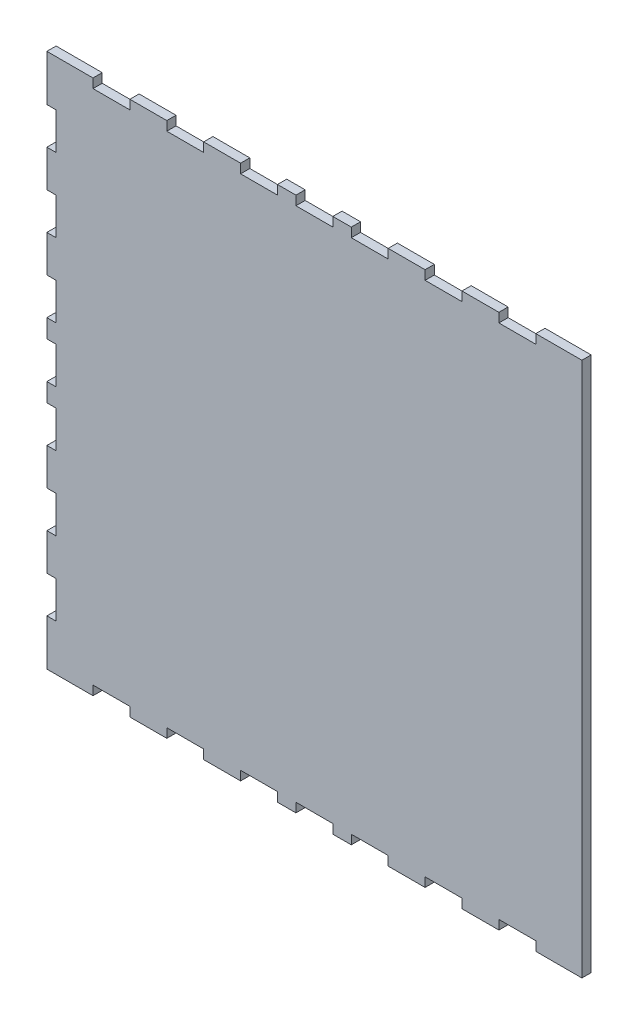
SolidWorks part; units mm, degrees
ref_plane "Front Plane" through (0, 0, 0) normal (0, 0, 1) x (1, 0, 0)
ref_plane "Top Plane" through (0, 0, 0) normal (0, 1, 0) x (1, 0, 0)
ref_plane "Right Plane" through (0, 0, 0) normal (1, 0, 0) x (0, 0, -1)
sketch "Sketch1" plane through (0, 0, 0) normal (0, 0, 1) x (1, 0, 0)
  line L0 (500.8156, 387.5892) -> (500.8156, 19.2892)
  line L1 (132.5156, 19.2892) -> (164.2656, 19.2892)
  line L2 (164.2656, 19.2892) -> (164.2656, 25.6392)
  line L3 (164.2656, 25.6392) -> (189.6656, 25.6392)
  line L4 (189.6656, 25.6392) -> (189.6656, 19.2892)
  line L5 (189.6656, 19.2892) -> (215.0656, 19.2892)
  line L6 (215.0656, 19.2892) -> (215.0656, 25.6392)
  line L7 (215.0656, 25.6392) -> (240.4656, 25.6392)
  line L8 (240.4656, 25.6392) -> (240.4656, 19.2892)
  line L9 (240.4656, 19.2892) -> (265.8656, 19.2892)
  line L10 (265.8656, 19.2892) -> (265.8656, 25.6392)
  line L11 (265.8656, 25.6392) -> (291.2656, 25.6392)
  line L12 (291.2656, 25.6392) -> (291.2656, 19.2892)
  line L13 (500.8156, 19.2892) -> (469.0656, 19.2892)
  line L14 (469.0656, 19.2892) -> (469.0656, 25.6392)
  line L15 (469.0656, 25.6392) -> (443.6656, 25.6392)
  line L16 (443.6656, 25.6392) -> (443.6656, 19.2892)
  line L17 (443.6656, 19.2892) -> (418.2656, 19.2892)
  line L18 (418.2656, 19.2892) -> (418.2656, 25.6392)
  line L19 (418.2656, 25.6392) -> (392.8656, 25.6392)
  line L20 (392.8656, 25.6392) -> (392.8656, 19.2892)
  line L21 (392.8656, 19.2892) -> (367.4656, 19.2892)
  line L22 (367.4656, 19.2892) -> (367.4656, 25.6392)
  line L23 (367.4656, 25.6392) -> (342.0656, 25.6392)
  line L24 (342.0656, 25.6392) -> (342.0656, 19.2892)
  line L25 (291.2656, 19.2892) -> (303.9656, 19.2892)
  line L26 (303.9656, 19.2892) -> (303.9656, 25.6392)
  line L27 (303.9656, 25.6392) -> (329.3656, 25.6392)
  line L28 (329.3656, 25.6392) -> (329.3656, 19.2892)
  line L29 (329.3656, 19.2892) -> (342.0656, 19.2892)
  line L30 (132.5156, 387.5892) -> (164.2656, 387.5892)
  line L31 (164.2656, 387.5892) -> (164.2656, 381.2392)
  line L32 (164.2656, 381.2392) -> (189.6656, 381.2392)
  line L33 (189.6656, 381.2392) -> (189.6656, 387.5892)
  line L34 (189.6656, 387.5892) -> (215.0656, 387.5892)
  line L35 (215.0656, 387.5892) -> (215.0656, 381.2392)
  line L36 (215.0656, 381.2392) -> (240.4656, 381.2392)
  line L37 (240.4656, 381.2392) -> (240.4656, 387.5892)
  line L38 (240.4656, 387.5892) -> (265.8656, 387.5892)
  line L39 (265.8656, 387.5892) -> (265.8656, 381.2392)
  line L40 (265.8656, 381.2392) -> (291.2656, 381.2392)
  line L41 (291.2656, 381.2392) -> (291.2656, 387.5892)
  line L42 (500.8156, 387.5892) -> (469.0656, 387.5892)
  line L43 (469.0656, 387.5892) -> (469.0656, 381.2392)
  line L44 (469.0656, 381.2392) -> (443.6656, 381.2392)
  line L45 (443.6656, 381.2392) -> (443.6656, 387.5892)
  line L46 (443.6656, 387.5892) -> (418.2656, 387.5892)
  line L47 (418.2656, 387.5892) -> (418.2656, 381.2392)
  line L48 (418.2656, 381.2392) -> (392.8656, 381.2392)
  line L49 (392.8656, 381.2392) -> (392.8656, 387.5892)
  line L50 (392.8656, 387.5892) -> (367.4656, 387.5892)
  line L51 (367.4656, 387.5892) -> (367.4656, 381.2392)
  line L52 (367.4656, 381.2392) -> (342.0656, 381.2392)
  line L53 (342.0656, 381.2392) -> (342.0656, 387.5892)
  line L54 (291.2656, 387.5892) -> (303.9656, 387.5892)
  line L55 (303.9656, 387.5892) -> (303.9656, 381.2392)
  line L56 (303.9656, 381.2392) -> (329.3656, 381.2392)
  line L57 (329.3656, 381.2392) -> (329.3656, 387.5892)
  line L58 (329.3656, 387.5892) -> (342.0656, 387.5892)
  line L59 (132.5156, 19.2892) -> (132.5156, 51.0392)
  line L60 (132.5156, 51.0392) -> (138.8656, 51.0392)
  line L61 (138.8656, 51.0392) -> (138.8656, 76.4392)
  line L62 (138.8656, 76.4392) -> (132.5156, 76.4392)
  line L63 (132.5156, 76.4392) -> (132.5156, 101.8392)
  line L64 (132.5156, 101.8392) -> (138.8656, 101.8392)
  line L65 (138.8656, 101.8392) -> (138.8656, 127.2392)
  line L66 (138.8656, 127.2392) -> (132.5156, 127.2392)
  line L67 (132.5156, 127.2392) -> (132.5156, 152.6392)
  line L68 (132.5156, 152.6392) -> (138.8656, 152.6392)
  line L69 (138.8656, 152.6392) -> (138.8656, 178.0392)
  line L70 (138.8656, 178.0392) -> (132.5156, 178.0392)
  line L71 (132.5156, 387.5892) -> (132.5156, 355.8392)
  line L72 (132.5156, 355.8392) -> (138.8656, 355.8392)
  line L73 (138.8656, 355.8392) -> (138.8656, 330.4392)
  line L74 (138.8656, 330.4392) -> (132.5156, 330.4392)
  line L75 (132.5156, 330.4392) -> (132.5156, 305.0392)
  line L76 (132.5156, 305.0392) -> (138.8656, 305.0392)
  line L77 (138.8656, 305.0392) -> (138.8656, 279.6392)
  line L78 (138.8656, 279.6392) -> (132.5156, 279.6392)
  line L79 (132.5156, 279.6392) -> (132.5156, 254.2392)
  line L80 (132.5156, 254.2392) -> (138.8656, 254.2392)
  line L81 (138.8656, 254.2392) -> (138.8656, 228.8392)
  line L82 (138.8656, 228.8392) -> (132.5156, 228.8392)
  line L83 (132.5156, 178.0392) -> (132.5156, 190.7392)
  line L84 (132.5156, 190.7392) -> (138.8656, 190.7392)
  line L85 (138.8656, 190.7392) -> (138.8656, 216.1392)
  line L86 (138.8656, 216.1392) -> (132.5156, 216.1392)
  line L87 (132.5156, 216.1392) -> (132.5156, 228.8392)
extrude "Extrude1" add sketch "Sketch1" along normal blind 6.35
